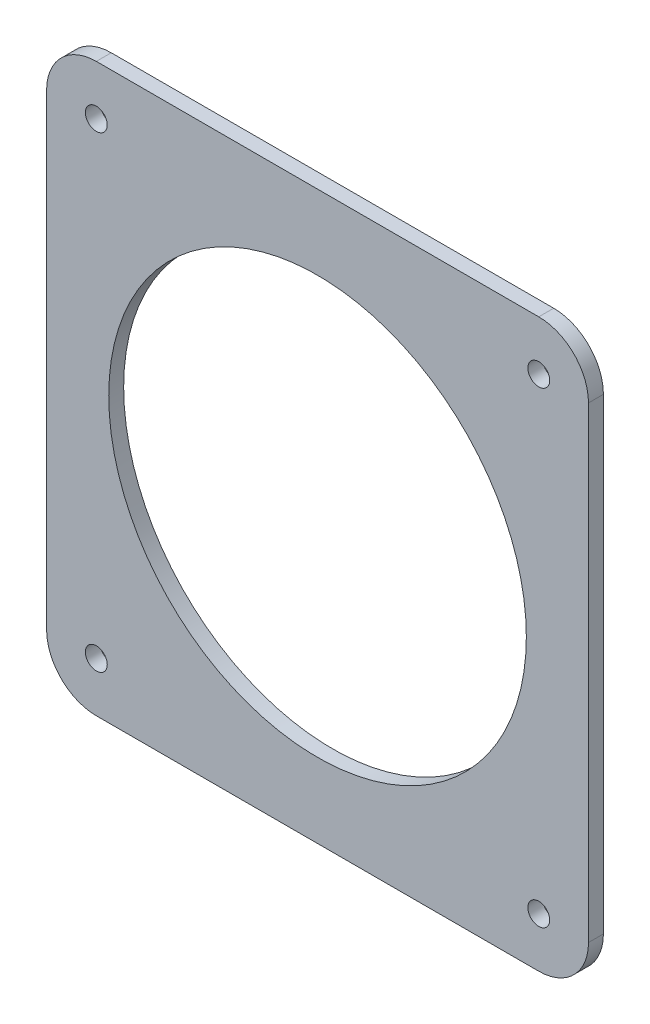
SolidWorks part; units mm, degrees
ref_plane "前视基准面" through (0, 0, 0) normal (0, 0, 1) x (1, 0, 0)
ref_plane "上视基准面" through (0, 0, 0) normal (0, 1, 0) x (1, 0, 0)
ref_plane "右视基准面" through (0, 0, 0) normal (1, 0, 0) x (0, 0, -1)
sketch "草图1" plane through (0, 0, 0) normal (0, 0, 1) x (1, 0, 0)
  line L0 (0, -57) -> (54.5, -57) construction
  line L1 (0, 0) -> (109, 0)
  line L2 (0, 0) -> (0, -114)
  line L3 (0, -114) -> (109, -114)
  line L4 (109, 0) -> (109, -114)
  line L9 (54.5, 0) -> (54.5, -114) construction
  line L10 (96.5, -57) -> (109, -57) construction
  circle A0 centre (99, -10) radius 2.2
  circle A1 centre (99, -104) radius 2.2
  circle A2 centre (10, -10) radius 2.2
  circle A3 centre (10, -104) radius 2.2
  circle A4 centre (54.5, -57) radius 42
  dimension "D3" = 10
  dimension "D4" = 10
  dimension "D11" = 89
  dimension "D1" = 109
  dimension "D2" = 114
  dimension "D5" = 2
  dimension "D6" = 2
extrude "凸台-拉伸1" add sketch "草图1" along normal blind 3
fillet "圆角3" radius 10 4 edges at (0, 0, 1.5) (0, -114, 1.5) (109, -114, 1.5) (109, 0, 1.5)
